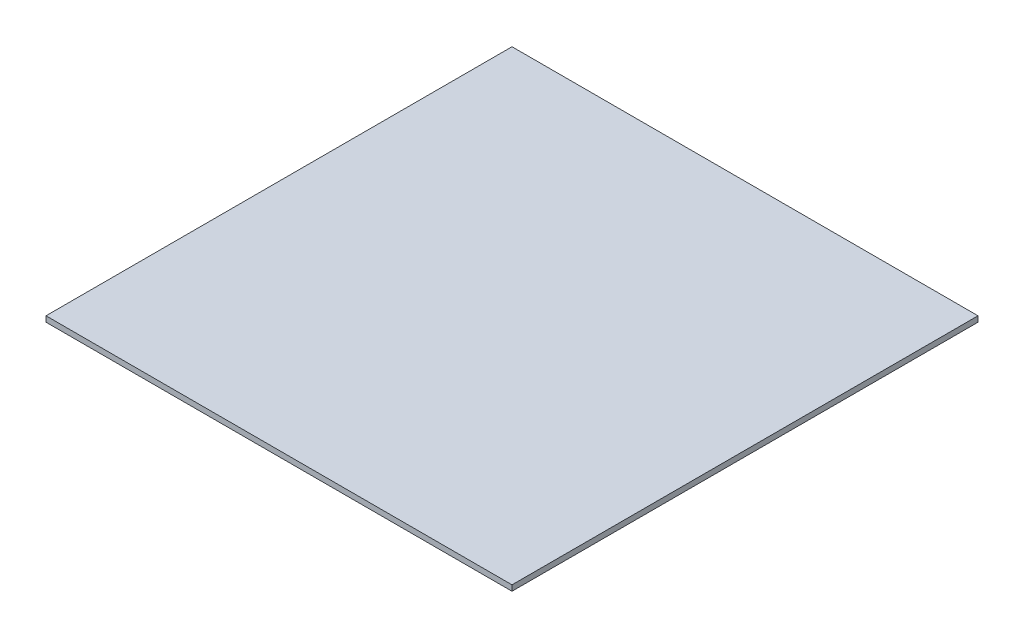
SolidWorks part; units mm, degrees
ref_plane "Front Plane" through (0, 0, 0) normal (0, 0, 1) x (1, 0, 0)
ref_plane "Top Plane" through (0, 0, 0) normal (0, 1, 0) x (1, 0, 0)
ref_plane "Right Plane" through (0, 0, 0) normal (1, 0, 0) x (0, 0, -1)
sketch "Sketch1" plane through (0, 0, 0) normal (0, 1, 0) x (1, 0, 0)
  line L1 (-125, 125) -> (125, 125)
  line L2 (-125, 125) -> (-125, -125)
  line L3 (-125, -125) -> (125, -125)
  line L4 (125, 125) -> (125, -125)
  line L5 (-125, 125) -> (125, -125) construction
  line L6 (-125, -125) -> (125, 125) construction
  point P0 (0, 0)
extrude "Boss-Extrude1" add sketch "Sketch1" along normal blind 3
